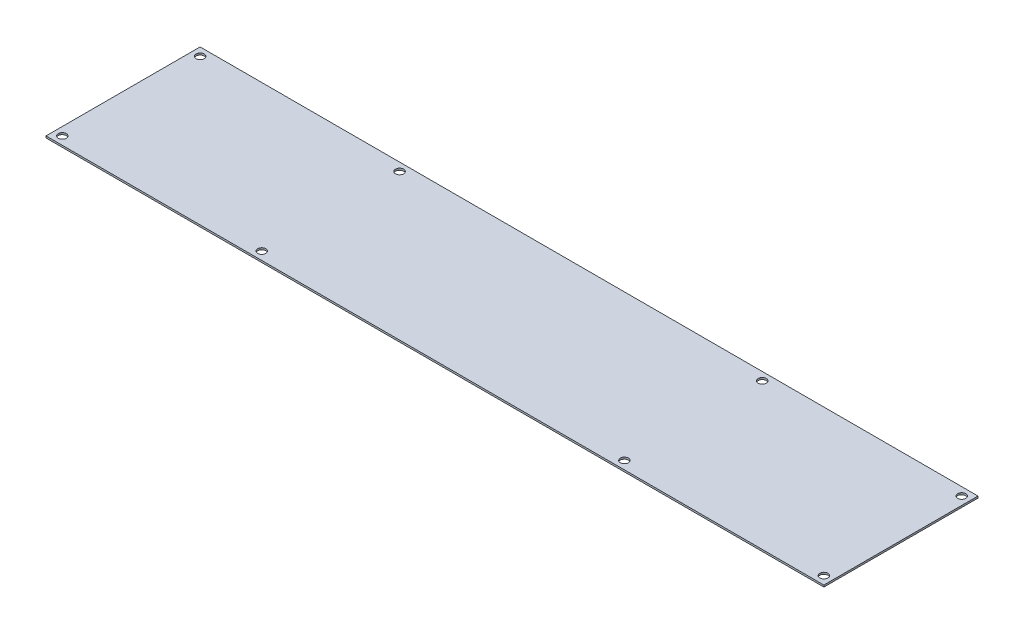
SolidWorks part; units mm, degrees
ref_plane "Front Plane" through (0, 0, 0) normal (0, 0, 1) x (1, 0, 0)
ref_plane "Top Plane" through (0, 0, 0) normal (0, 1, 0) x (1, 0, 0)
ref_plane "Right Plane" through (0, 0, 0) normal (1, 0, 0) x (0, 0, -1)
sketch "Sketch1" plane through (0, 0, 0) normal (0, 1, 0) x (1, 0, 0)
  line L1 (-214.5, -42.5) -> (214.5, -42.5)
  line L2 (-214.5, -42.5) -> (-214.5, 42.5)
  line L3 (-214.5, 42.5) -> (214.5, 42.5)
  line L4 (214.5, -42.5) -> (214.5, 42.5)
  line L5 (-214.5, -42.5) -> (214.5, 42.5) construction
  line L6 (-214.5, 42.5) -> (214.5, -42.5) construction
  point P0 (0, 0)
  dimension "D1" = 429
  dimension "D2" = 85
extrude "Boss-Extrude1" add sketch "Sketch1" along normal blind 1
hole_wizard "M4 Clearance Hole1" positions "Sketch2" profile "Sketch3" hole size "M4" standard "ANSI Metric" end condition through all
sketch "Sketch2" plane through (0, 1, 0) normal (0, 1, 0) x (1, 0, 0)
  line L0 (214.5, 42.5) -> (-214.5, 42.5) construction
  line L1 (-214.5, 42.5) -> (-214.5, -42.5) construction
  line L2 (0, -0.55) -> (0, 0.55) construction
  line L4 (-100, 38) -> (100, 38)
  line L5 (-0.55, 0) -> (0.55, 0) construction
  line L6 (-100, -38) -> (100, -38)
  point P0 (-210, 38)
  point P9 (210, 38)
  point P12 (-100, 38)
  point P13 (100, 38)
  point P21 (0, 38)
  point P27 (100, -38)
  point P28 (-100, -38)
  point P29 (210, -38)
  point P30 (-210, -38)
  dimension "D1" = 4.5
  dimension "D2" = 4.5
  dimension "D3" = 200
sketch "Sketch3" plane through (-210, 1, -38) normal (1, 0, 0) x (0, 0, 1)
  line L0 (0, 0) -> (0, 1)
  line L1 (0, 1) -> (2.25, 1)
  line L2 (2.25, 1) -> (2.25, 0)
  line L5 (2.25, 0) -> (0, 0)
  line L11 (0, -6.35) -> (0, 107.95) construction
  dimension "Thru Hole Dia." = 4.5
  dimension "Thru Hole Depth" = 1
